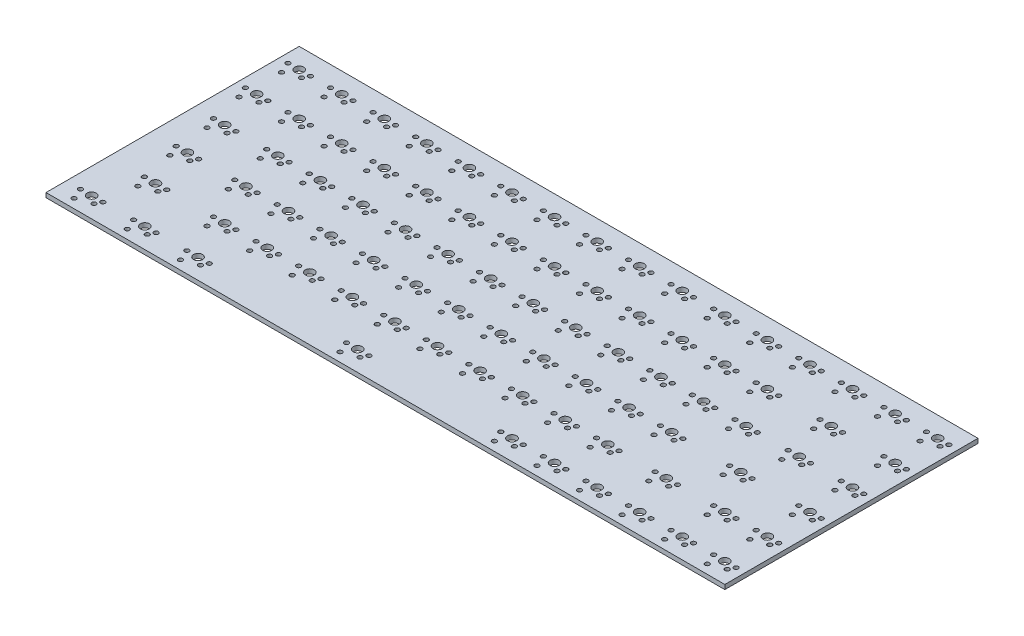
SolidWorks part; units mm, degrees
ref_plane "Спереди" through (0, 0, 0) normal (0, 0, 1) x (1, 0, 0)
ref_plane "Сверху" through (0, 0, 0) normal (0, 1, 0) x (1, 0, 0)
ref_plane "Справа" through (0, 0, 0) normal (1, 0, 0) x (0, 0, -1)
sketch "Эскиз1" plane through (0, 0, 0) normal (0, 1, 0) x (1, 0, 0)
  line L1 (-9, 9) -> (294, 9)
  line L2 (-9, 9) -> (-9, -104)
  line L3 (-9, -104) -> (294, -104)
  line L4 (294, 9) -> (294, -104)
  circle A1 centre (3.65, -2.6) radius 1
  circle A2 centre (5, 0) radius 1
  circle A7 centre (-2.8676, -5) radius 1
  circle A8 centre (-5, 0) radius 1
  circle A9 centre (0, 0) radius 2
  circle A10 centre (22.65, -2.6) radius 1
  circle A11 centre (24, 0) radius 1
  circle A12 centre (16.1324, -5) radius 1
  circle A13 centre (14, 0) radius 1
  circle A14 centre (19, 0) radius 2
  circle A15 centre (41.65, -2.6) radius 1
  circle A16 centre (43, 0) radius 1
  circle A17 centre (35.1324, -5) radius 1
  circle A18 centre (33, 0) radius 1
  circle A19 centre (38, 0) radius 2
  circle A20 centre (60.65, -2.6) radius 1
  circle A21 centre (62, 0) radius 1
  circle A22 centre (54.1324, -5) radius 1
  circle A23 centre (52, 0) radius 1
  circle A24 centre (57, 0) radius 2
  circle A25 centre (79.65, -2.6) radius 1
  circle A26 centre (81, 0) radius 1
  circle A27 centre (73.1324, -5) radius 1
  circle A28 centre (71, 0) radius 1
  circle A29 centre (76, 0) radius 2
  circle A30 centre (98.65, -2.6) radius 1
  circle A31 centre (100, 0) radius 1
  circle A32 centre (92.1324, -5) radius 1
  circle A33 centre (90, 0) radius 1
  circle A34 centre (95, 0) radius 2
  circle A35 centre (117.65, -2.6) radius 1
  circle A36 centre (119, 0) radius 1
  circle A37 centre (111.1324, -5) radius 1
  circle A38 centre (109, 0) radius 1
  circle A39 centre (114, 0) radius 2
  circle A40 centre (136.65, -2.6) radius 1
  circle A41 centre (138, 0) radius 1
  circle A42 centre (130.1324, -5) radius 1
  circle A43 centre (128, 0) radius 1
  circle A44 centre (133, 0) radius 2
  circle A45 centre (155.65, -2.6) radius 1
  circle A46 centre (157, 0) radius 1
  circle A47 centre (149.1324, -5) radius 1
  circle A48 centre (147, 0) radius 1
  circle A49 centre (152, 0) radius 2
  circle A50 centre (174.65, -2.6) radius 1
  circle A51 centre (176, 0) radius 1
  circle A52 centre (168.1324, -5) radius 1
  circle A53 centre (166, 0) radius 1
  circle A54 centre (171, 0) radius 2
  circle A55 centre (193.65, -2.6) radius 1
  circle A56 centre (195, 0) radius 1
  circle A57 centre (187.1324, -5) radius 1
  circle A58 centre (185, 0) radius 1
  circle A59 centre (190, 0) radius 2
  circle A60 centre (212.65, -2.6) radius 1
  circle A61 centre (214, 0) radius 1
  circle A62 centre (206.1324, -5) radius 1
  circle A63 centre (204, 0) radius 1
  circle A64 centre (209, 0) radius 2
  circle A65 centre (212.65, -21.6) radius 1
  circle A66 centre (214, -19) radius 1
  circle A67 centre (206.1324, -24) radius 1
  circle A68 centre (204, -19) radius 1
  circle A69 centre (209, -19) radius 2
  circle A70 centre (193.65, -21.6) radius 1
  circle A71 centre (195, -19) radius 1
  circle A72 centre (187.1324, -24) radius 1
  circle A73 centre (185, -19) radius 1
  circle A74 centre (190, -19) radius 2
  circle A75 centre (174.65, -21.6) radius 1
  circle A76 centre (176, -19) radius 1
  circle A77 centre (168.1324, -24) radius 1
  circle A78 centre (166, -19) radius 1
  circle A79 centre (171, -19) radius 2
  circle A80 centre (155.65, -21.6) radius 1
  circle A81 centre (157, -19) radius 1
  circle A82 centre (149.1324, -24) radius 1
  circle A83 centre (147, -19) radius 1
  circle A84 centre (152, -19) radius 2
  circle A85 centre (136.65, -21.6) radius 1
  circle A86 centre (138, -19) radius 1
  circle A87 centre (130.1324, -24) radius 1
  circle A88 centre (128, -19) radius 1
  circle A89 centre (133, -19) radius 2
  circle A90 centre (117.65, -21.6) radius 1
  circle A91 centre (119, -19) radius 1
  circle A92 centre (111.1324, -24) radius 1
  circle A93 centre (109, -19) radius 1
  circle A94 centre (114, -19) radius 2
  circle A95 centre (98.65, -21.6) radius 1
  circle A96 centre (100, -19) radius 1
  circle A97 centre (92.1324, -24) radius 1
  circle A98 centre (90, -19) radius 1
  circle A99 centre (95, -19) radius 2
  circle A100 centre (79.65, -21.6) radius 1
  circle A101 centre (81, -19) radius 1
  circle A102 centre (73.1324, -24) radius 1
  circle A103 centre (71, -19) radius 1
  circle A104 centre (76, -19) radius 2
  circle A105 centre (60.65, -21.6) radius 1
  circle A106 centre (62, -19) radius 1
  circle A107 centre (54.1324, -24) radius 1
  circle A108 centre (52, -19) radius 1
  circle A109 centre (57, -19) radius 2
  circle A110 centre (41.65, -21.6) radius 1
  circle A111 centre (43, -19) radius 1
  circle A112 centre (35.1324, -24) radius 1
  circle A113 centre (33, -19) radius 1
  circle A114 centre (38, -19) radius 2
  circle A115 centre (22.65, -21.6) radius 1
  circle A116 centre (24, -19) radius 1
  circle A117 centre (16.1324, -24) radius 1
  circle A118 centre (14, -19) radius 1
  circle A119 centre (19, -19) radius 2
  circle A120 centre (3.65, -21.6) radius 1
  circle A121 centre (5, -19) radius 1
  circle A122 centre (-2.8676, -24) radius 1
  circle A123 centre (-5, -19) radius 1
  circle A124 centre (0, -19) radius 2
  circle A125 centre (8.4, -40.6) radius 1
  circle A126 centre (9.75, -38) radius 1
  circle A127 centre (1.8824, -43) radius 1
  circle A128 centre (-0.25, -38) radius 1
  circle A129 centre (4.75, -38) radius 2
  circle A130 centre (32.15, -40.6) radius 1
  circle A131 centre (33.5, -38) radius 1
  circle A132 centre (25.6324, -43) radius 1
  circle A133 centre (23.5, -38) radius 1
  circle A134 centre (28.5, -38) radius 2
  circle A135 centre (51.15, -40.6) radius 1
  circle A136 centre (52.5, -38) radius 1
  circle A137 centre (44.6324, -43) radius 1
  circle A138 centre (42.5, -38) radius 1
  circle A139 centre (47.5, -38) radius 2
  circle A140 centre (70.15, -40.6) radius 1
  circle A141 centre (71.5, -38) radius 1
  circle A142 centre (63.6324, -43) radius 1
  circle A143 centre (61.5, -38) radius 1
  circle A144 centre (66.5, -38) radius 2
  circle A145 centre (89.15, -40.6) radius 1
  circle A146 centre (90.5, -38) radius 1
  circle A147 centre (82.6324, -43) radius 1
  circle A148 centre (80.5, -38) radius 1
  circle A149 centre (85.5, -38) radius 2
  circle A150 centre (104.5, -38) radius 2
  circle A151 centre (109.5, -38) radius 1
  circle A152 centre (99.5, -38) radius 1
  circle A153 centre (101.6324, -43) radius 1
  circle A154 centre (108.15, -40.6) radius 1
  circle A155 centre (123.5, -38) radius 2
  circle A156 centre (128.5, -38) radius 1
  circle A157 centre (118.5, -38) radius 1
  circle A158 centre (120.6324, -43) radius 1
  circle A159 centre (127.15, -40.6) radius 1
  circle A160 centre (142.5, -38) radius 2
  circle A161 centre (147.5, -38) radius 1
  circle A162 centre (137.5, -38) radius 1
  circle A163 centre (139.6324, -43) radius 1
  circle A164 centre (146.15, -40.6) radius 1
  circle A165 centre (161.5, -38) radius 2
  circle A166 centre (166.5, -38) radius 1
  circle A167 centre (156.5, -38) radius 1
  circle A168 centre (158.6324, -43) radius 1
  circle A169 centre (165.15, -40.6) radius 1
  circle A170 centre (180.5, -38) radius 2
  circle A171 centre (185.5, -38) radius 1
  circle A172 centre (175.5, -38) radius 1
  circle A173 centre (177.6324, -43) radius 1
  circle A174 centre (184.15, -40.6) radius 1
  circle A175 centre (199.5, -38) radius 2
  circle A176 centre (204.5, -38) radius 1
  circle A177 centre (194.5, -38) radius 1
  circle A178 centre (196.6324, -43) radius 1
  circle A179 centre (203.15, -40.6) radius 1
  circle A180 centre (204.25, -57) radius 2
  circle A181 centre (209.25, -57) radius 1
  circle A182 centre (199.25, -57) radius 1
  circle A183 centre (201.3824, -62) radius 1
  circle A184 centre (207.9, -59.6) radius 1
  circle A185 centre (185.25, -57) radius 2
  circle A186 centre (190.25, -57) radius 1
  circle A187 centre (180.25, -57) radius 1
  circle A188 centre (182.3824, -62) radius 1
  circle A189 centre (188.9, -59.6) radius 1
  circle A190 centre (166.25, -57) radius 2
  circle A191 centre (171.25, -57) radius 1
  circle A192 centre (161.25, -57) radius 1
  circle A193 centre (163.3824, -62) radius 1
  circle A194 centre (169.9, -59.6) radius 1
  circle A195 centre (147.25, -57) radius 2
  circle A196 centre (152.25, -57) radius 1
  circle A197 centre (142.25, -57) radius 1
  circle A198 centre (144.3824, -62) radius 1
  circle A199 centre (150.9, -59.6) radius 1
  circle A200 centre (128.25, -57) radius 2
  circle A201 centre (133.25, -57) radius 1
  circle A202 centre (123.25, -57) radius 1
  circle A203 centre (125.3824, -62) radius 1
  circle A204 centre (131.9, -59.6) radius 1
  circle A205 centre (109.25, -57) radius 2
  circle A206 centre (114.25, -57) radius 1
  circle A207 centre (104.25, -57) radius 1
  circle A208 centre (106.3824, -62) radius 1
  circle A209 centre (112.9, -59.6) radius 1
  circle A210 centre (90.25, -57) radius 2
  circle A211 centre (95.25, -57) radius 1
  circle A212 centre (85.25, -57) radius 1
  circle A213 centre (87.3824, -62) radius 1
  circle A214 centre (93.9, -59.6) radius 1
  circle A215 centre (71.25, -57) radius 2
  circle A216 centre (76.25, -57) radius 1
  circle A217 centre (66.25, -57) radius 1
  circle A218 centre (68.3824, -62) radius 1
  circle A219 centre (74.9, -59.6) radius 1
  circle A220 centre (52.25, -57) radius 2
  circle A221 centre (57.25, -57) radius 1
  circle A222 centre (47.25, -57) radius 1
  circle A223 centre (49.3824, -62) radius 1
  circle A224 centre (55.9, -59.6) radius 1
  circle A225 centre (33.25, -57) radius 2
  circle A226 centre (38.25, -57) radius 1
  circle A227 centre (28.25, -57) radius 1
  circle A228 centre (30.3824, -62) radius 1
  circle A229 centre (36.9, -59.6) radius 1
  circle A230 centre (7.125, -57) radius 2
  circle A231 centre (12.125, -57) radius 1
  circle A232 centre (2.125, -57) radius 1
  circle A233 centre (4.2574, -62) radius 1
  circle A234 centre (10.775, -59.6) radius 1
  circle A235 centre (11.875, -76) radius 2
  circle A236 centre (16.875, -76) radius 1
  circle A237 centre (6.875, -76) radius 1
  circle A238 centre (9.0074, -81) radius 1
  circle A239 centre (15.525, -78.6) radius 1
  circle A240 centre (42.75, -76) radius 2
  circle A241 centre (47.75, -76) radius 1
  circle A242 centre (37.75, -76) radius 1
  circle A243 centre (39.8824, -81) radius 1
  circle A244 centre (46.4, -78.6) radius 1
  circle A245 centre (61.75, -76) radius 2
  circle A246 centre (66.75, -76) radius 1
  circle A247 centre (56.75, -76) radius 1
  circle A248 centre (58.8824, -81) radius 1
  circle A249 centre (65.4, -78.6) radius 1
  circle A250 centre (80.75, -76) radius 2
  circle A251 centre (85.75, -76) radius 1
  circle A252 centre (75.75, -76) radius 1
  circle A253 centre (77.8824, -81) radius 1
  circle A254 centre (84.4, -78.6) radius 1
  circle A255 centre (99.75, -76) radius 2
  circle A256 centre (104.75, -76) radius 1
  circle A257 centre (94.75, -76) radius 1
  circle A258 centre (96.8824, -81) radius 1
  circle A259 centre (103.4, -78.6) radius 1
  circle A260 centre (118.75, -76) radius 2
  circle A261 centre (123.75, -76) radius 1
  circle A262 centre (113.75, -76) radius 1
  circle A263 centre (115.8824, -81) radius 1
  circle A264 centre (122.4, -78.6) radius 1
  circle A265 centre (137.75, -76) radius 2
  circle A266 centre (142.75, -76) radius 1
  circle A267 centre (132.75, -76) radius 1
  circle A268 centre (134.8824, -81) radius 1
  circle A269 centre (141.4, -78.6) radius 1
  circle A270 centre (156.75, -76) radius 2
  circle A271 centre (161.75, -76) radius 1
  circle A272 centre (151.75, -76) radius 1
  circle A273 centre (153.8824, -81) radius 1
  circle A274 centre (160.4, -78.6) radius 1
  circle A275 centre (175.75, -76) radius 2
  circle A276 centre (180.75, -76) radius 1
  circle A277 centre (170.75, -76) radius 1
  circle A278 centre (172.8824, -81) radius 1
  circle A279 centre (179.4, -78.6) radius 1
  circle A280 centre (194.75, -76) radius 2
  circle A281 centre (199.75, -76) radius 1
  circle A282 centre (189.75, -76) radius 1
  circle A283 centre (191.8824, -81) radius 1
  circle A284 centre (198.4, -78.6) radius 1
  circle A285 centre (213.75, -76) radius 2
  circle A286 centre (218.75, -76) radius 1
  circle A287 centre (208.75, -76) radius 1
  circle A288 centre (210.8824, -81) radius 1
  circle A289 centre (217.4, -78.6) radius 1
  circle A290 centre (239.875, -76) radius 2
  circle A291 centre (244.875, -76) radius 1
  circle A292 centre (234.875, -76) radius 1
  circle A293 centre (237.0074, -81) radius 1
  circle A294 centre (243.525, -78.6) radius 1
  circle A295 centre (2.375, -95) radius 2
  circle A296 centre (7.375, -95) radius 1
  circle A297 centre (-2.625, -95) radius 1
  circle A298 centre (-0.4926, -100) radius 1
  circle A299 centre (6.025, -97.6) radius 1
  circle A300 centre (26.125, -95) radius 2
  circle A301 centre (31.125, -95) radius 1
  circle A302 centre (21.125, -95) radius 1
  circle A303 centre (23.2574, -100) radius 1
  circle A304 centre (29.775, -97.6) radius 1
  circle A305 centre (49.875, -95) radius 2
  circle A306 centre (54.875, -95) radius 1
  circle A307 centre (44.875, -95) radius 1
  circle A308 centre (47.0074, -100) radius 1
  circle A309 centre (53.525, -97.6) radius 1
  circle A310 centre (121.125, -95) radius 2
  circle A311 centre (126.125, -95) radius 1
  circle A312 centre (116.125, -95) radius 1
  circle A313 centre (118.2574, -100) radius 1
  circle A314 centre (124.775, -97.6) radius 1
  circle A315 centre (190, -95) radius 2
  circle A316 centre (195, -95) radius 1
  circle A317 centre (185, -95) radius 1
  circle A318 centre (187.1324, -100) radius 1
  circle A319 centre (193.65, -97.6) radius 1
  circle A320 centre (209, -95) radius 2
  circle A321 centre (214, -95) radius 1
  circle A322 centre (204, -95) radius 1
  circle A323 centre (206.1324, -100) radius 1
  circle A324 centre (212.65, -97.6) radius 1
  circle A325 centre (228, -95) radius 2
  circle A326 centre (233, -95) radius 1
  circle A327 centre (223, -95) radius 1
  circle A328 centre (225.1324, -100) radius 1
  circle A329 centre (231.65, -97.6) radius 1
  circle A330 centre (247, -95) radius 2
  circle A331 centre (252, -95) radius 1
  circle A332 centre (242, -95) radius 1
  circle A333 centre (244.1324, -100) radius 1
  circle A334 centre (250.65, -97.6) radius 1
  circle A335 centre (266, -95) radius 2
  circle A336 centre (271, -95) radius 1
  circle A337 centre (261, -95) radius 1
  circle A338 centre (263.1324, -100) radius 1
  circle A339 centre (269.65, -97.6) radius 1
  circle A340 centre (266, -76) radius 2
  circle A341 centre (271, -76) radius 1
  circle A342 centre (261, -76) radius 1
  circle A343 centre (263.1324, -81) radius 1
  circle A344 centre (269.65, -78.6) radius 1
  circle A345 centre (254.125, -57) radius 2
  circle A346 centre (259.125, -57) radius 1
  circle A347 centre (249.125, -57) radius 1
  circle A348 centre (251.2574, -62) radius 1
  circle A349 centre (257.775, -59.6) radius 1
  circle A350 centre (223.25, -57) radius 2
  circle A351 centre (228.25, -57) radius 1
  circle A352 centre (218.25, -57) radius 1
  circle A353 centre (220.3824, -62) radius 1
  circle A354 centre (226.9, -59.6) radius 1
  circle A355 centre (218.5, -38) radius 2
  circle A356 centre (223.5, -38) radius 1
  circle A357 centre (213.5, -38) radius 1
  circle A358 centre (215.6324, -43) radius 1
  circle A359 centre (222.15, -40.6) radius 1
  circle A360 centre (237.5, -38) radius 2
  circle A361 centre (242.5, -38) radius 1
  circle A362 centre (232.5, -38) radius 1
  circle A363 centre (234.6324, -43) radius 1
  circle A364 centre (241.15, -40.6) radius 1
  circle A365 centre (261.25, -38) radius 2
  circle A366 centre (266.25, -38) radius 1
  circle A367 centre (256.25, -38) radius 1
  circle A368 centre (258.3824, -43) radius 1
  circle A369 centre (264.9, -40.6) radius 1
  circle A370 centre (256.5, -19) radius 2
  circle A371 centre (261.5, -19) radius 1
  circle A372 centre (251.5, -19) radius 1
  circle A373 centre (253.6324, -24) radius 1
  circle A374 centre (260.15, -21.6) radius 1
  circle A375 centre (228, -19) radius 2
  circle A376 centre (233, -19) radius 1
  circle A377 centre (223, -19) radius 1
  circle A378 centre (225.1324, -24) radius 1
  circle A379 centre (231.65, -21.6) radius 1
  circle A380 centre (228, 0) radius 2
  circle A381 centre (233, 0) radius 1
  circle A382 centre (223, 0) radius 1
  circle A383 centre (225.1324, -5) radius 1
  circle A384 centre (231.65, -2.6) radius 1
  circle A385 centre (247, 0) radius 2
  circle A386 centre (252, 0) radius 1
  circle A387 centre (242, 0) radius 1
  circle A388 centre (244.1324, -5) radius 1
  circle A389 centre (250.65, -2.6) radius 1
  circle A390 centre (266, 0) radius 2
  circle A391 centre (271, 0) radius 1
  circle A392 centre (261, 0) radius 1
  circle A393 centre (263.1324, -5) radius 1
  circle A394 centre (269.65, -2.6) radius 1
  circle A395 centre (285, -95) radius 2
  circle A396 centre (290, -95) radius 1
  circle A397 centre (280, -95) radius 1
  circle A398 centre (282.1324, -100) radius 1
  circle A399 centre (288.65, -97.6) radius 1
  circle A400 centre (285, -76) radius 2
  circle A401 centre (290, -76) radius 1
  circle A402 centre (280, -76) radius 1
  circle A403 centre (282.1324, -81) radius 1
  circle A404 centre (288.65, -78.6) radius 1
  circle A405 centre (285, -57) radius 2
  circle A406 centre (290, -57) radius 1
  circle A407 centre (280, -57) radius 1
  circle A408 centre (282.1324, -62) radius 1
  circle A409 centre (288.65, -59.6) radius 1
  circle A410 centre (285, -38) radius 2
  circle A411 centre (290, -38) radius 1
  circle A412 centre (280, -38) radius 1
  circle A413 centre (282.1324, -43) radius 1
  circle A414 centre (288.65, -40.6) radius 1
  circle A415 centre (285, -19) radius 2
  circle A416 centre (290, -19) radius 1
  circle A417 centre (280, -19) radius 1
  circle A418 centre (282.1324, -24) radius 1
  circle A419 centre (288.65, -21.6) radius 1
  circle A420 centre (285, 0) radius 2
  circle A421 centre (290, 0) radius 1
  circle A422 centre (280, 0) radius 1
  circle A423 centre (282.1324, -5) radius 1
  circle A424 centre (288.65, -2.6) radius 1
  point P0 (0, 0)
  point P1 (266, -19)
  point P3 (247, -19)
  point P5 (19, 0)
  point P6 (38, 0)
  point P7 (57, 0)
  point P8 (76, 0)
  point P9 (95, 0)
  point P10 (114, 0)
  point P11 (133, 0)
  point P12 (152, 0)
  point P13 (171, 0)
  point P14 (190, 0)
  point P15 (209, 0)
  point P16 (228, 0)
  point P17 (247, 0)
  point P18 (266, 0)
  point P19 (285, 0)
  point P20 (19, -19)
  point P21 (38, -19)
  point P22 (57, -19)
  point P23 (76, -19)
  point P24 (95, -19)
  point P25 (114, -19)
  point P26 (133, -19)
  point P27 (152, -19)
  point P28 (171, -19)
  point P29 (190, -19)
  point P30 (209, -19)
  point P31 (228, -19)
  point P32 (266, -76)
  point P33 (285, -38)
  point P34 (285, -19)
  point P35 (0, -19)
  point P36 (285, -57)
  point P37 (285, -76)
  point P38 (285, -95)
  point P39 (266, -95)
  point P40 (247, -95)
  point P41 (228, -95)
  point P42 (209, -95)
  point P43 (190, -95)
  point P47 (4.75, -38)
  point P48 (7.125, -57)
  point P49 (11.875, -76)
  point P50 (2.375, -95)
  point P51 (42.75, -76)
  point P52 (26.125, -95)
  point P53 (49.875, -95)
  point P54 (33.25, -57)
  point P55 (28.5, -38)
  point P56 (261.25, -38)
  point P57 (61.75, -76)
  point P58 (47.5, -38)
  point P59 (66.5, -38)
  point P60 (85.5, -38)
  point P61 (104.5, -38)
  point P62 (123.5, -38)
  point P63 (142.5, -38)
  point P64 (161.5, -38)
  point P65 (180.5, -38)
  point P66 (199.5, -38)
  point P67 (218.5, -38)
  point P68 (237.5, -38)
  point P69 (52.25, -57)
  point P70 (71.25, -57)
  point P71 (90.25, -57)
  point P72 (109.25, -57)
  point P73 (128.25, -57)
  point P74 (147.25, -57)
  point P75 (166.25, -57)
  point P76 (185.25, -57)
  point P77 (204.25, -57)
  point P78 (223.25, -57)
  point P79 (80.75, -76)
  point P80 (99.75, -76)
  point P81 (118.75, -76)
  point P82 (137.75, -76)
  point P83 (156.75, -76)
  point P84 (175.75, -76)
  point P85 (194.75, -76)
  point P86 (213.75, -76)
  point P87 (254.125, -57)
  point P88 (239.875, -76)
  point P89 (256.5, -19)
  point P90 (121.125, -95)
  dimension "D6" = 19
  dimension "D7" = 113
  dimension "D8" = 19
  dimension "D9" = 9
  dimension "D10" = 9
  dimension "D11" = 303
  dimension "D12" = 13.75
  dimension "D13" = 16.125
  dimension "D14" = 20.875
  dimension "D15" = 11.375
  dimension "D17" = 23.75
  dimension "D18" = 26.125
  dimension "D19" = 30.875
  dimension "D25" = 71.25
  dimension "D26" = 28
  dimension "D27" = 9
  dimension "D28" = 9
  dimension "D29" = 9
  dimension "D30" = 28.5
  dimension "D31" = 23.75
  dimension "D32" = 30.875
  dimension "D33" = 26.125
  dimension "D1" = 16
  dimension "D2" = 2
  dimension "D3" = 5
  dimension "D4" = 2
  dimension "D5" = 6
  dimension "D16" = 3
  dimension "D20" = 12
  dimension "D21" = 11
  dimension "D22" = 10
extrude "Бобышка-Вытянуть1" add sketch "Эскиз1" along normal blind 2
